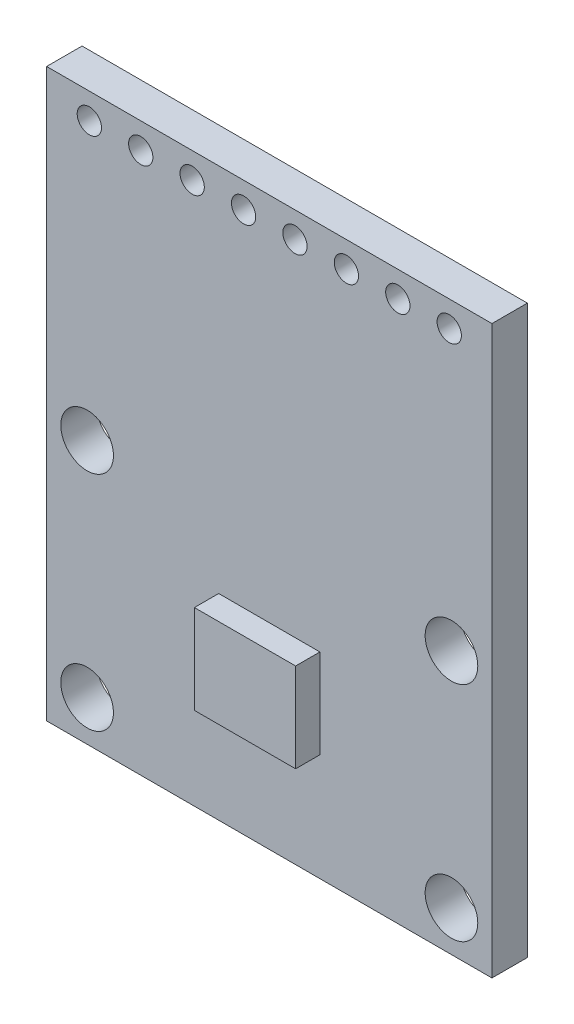
SolidWorks part; units mm, degrees
ref_plane "Front Plane" through (0, 0, 0) normal (0, 0, 1) x (1, 0, 0)
ref_plane "Top Plane" through (0, 0, 0) normal (0, 1, 0) x (1, 0, 0)
ref_plane "Right Plane" through (0, 0, 0) normal (1, 0, 0) x (0, 0, -1)
sketch "Sketch1" plane through (0, 0, 0) normal (0, 0, 1) x (1, 0, 0)
  line L1 (-11, -14) -> (11, -14)
  line L2 (-11, -14) -> (-11, 14)
  line L3 (-11, 14) -> (11, 14)
  line L4 (11, -14) -> (11, 14)
  line L5 (-11, -14) -> (11, 14) construction
  line L6 (-11, 14) -> (11, -14) construction
  point P0 (0, 0)
  dimension "D1" = 22
  dimension "D2" = 28
extrude "Boss-Extrude1" add sketch "Sketch1" along normal blind 1.75
sketch "Sketch2" plane through (0, 0, 1.75) normal (0, 0, 1) x (1, 0, 0)
  line L0 (0, -1000) -> (0, 49000) construction
  line L1 (-1000, -6.5) -> (49000, -6.5) construction
  line L3 (-9, -12) -> (9, -12) construction
  line L4 (-9, -12) -> (-9, -1) construction
  line L5 (-9, -1) -> (9, -1) construction
  line L6 (9, -12) -> (9, -1) construction
  line L7 (-9, -12) -> (9, -1) construction
  line L8 (-9, -1) -> (9, -12) construction
  circle A0 centre (-9, -1) radius 1.3
  circle A1 centre (-9, -12) radius 1.3
  circle A2 centre (9, -12) radius 1.3
  circle A3 centre (9, -1) radius 1.3
  circle A4 centre (0, -6.5) radius 1
  point P4 (0, -6.5)
  dimension "D4" = 2.6
  dimension "D5" = 2.6
  dimension "D6" = 2.6
  dimension "D7" = 2.6
  dimension "D8" = 2
  dimension "D1" = 6.5
  dimension "D2" = 18
  dimension "D3" = 11
extrude "Cut-Extrude1" cut sketch "Sketch2" against normal through all
sketch "Sketch3" plane through (0, 0, 1.75) normal (0, 0, 1) x (1, 0, 0)
  line L0 (11, 14) -> (-11, 14) construction
  circle A0 centre (-1.27, 12.73) radius 0.6
  dimension "D1" = 1.27
  dimension "D2" = 1.27
extrude "Cut-Extrude2" cut sketch "Sketch3" against normal through all
pattern_linear "LPattern1" count 4 spacing 2.54 along (-1, 0, 0) of "Cut-Extrude2"
mirror "Mirror1" about plane through (0, 0, 0) normal (1, 0, 0) of "LPattern1", "Cut-Extrude2"
sketch "Sketch4" plane through (0, 0, 1.75) normal (0, 0, 1) x (1, 0, 0)
  line L1 (-2.5, -8.7) -> (2.5, -8.7)
  line L2 (-2.5, -8.7) -> (-2.5, -4.3)
  line L3 (-2.5, -4.3) -> (2.5, -4.3)
  line L4 (2.5, -8.7) -> (2.5, -4.3)
  line L5 (-2.5, -8.7) -> (2.5, -4.3) construction
  line L6 (-2.5, -4.3) -> (2.5, -8.7) construction
  point P0 (0, -6.5)
  dimension "D1" = 5
  dimension "D2" = 4.4
extrude "Boss-Extrude2" add sketch "Sketch4" along normal blind 1.2
